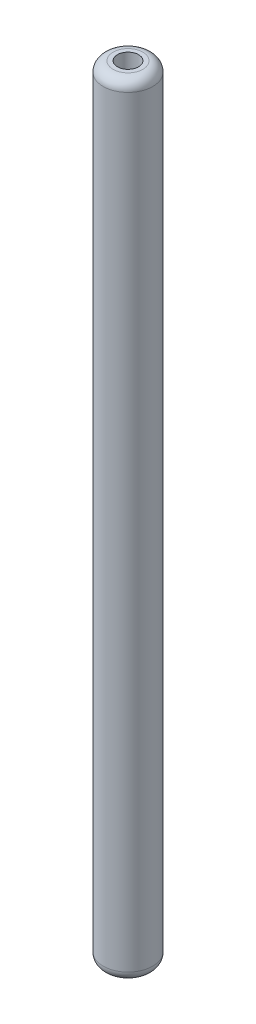
SolidWorks part; units mm, degrees
ref_plane "Front Plane" through (0, 0, 0) normal (0, 0, 1) x (1, 0, 0)
ref_plane "Top Plane" through (0, 0, 0) normal (0, 1, 0) x (1, 0, 0)
ref_plane "Right Plane" through (0, 0, 0) normal (1, 0, 0) x (0, 0, -1)
sketch "Sketch1" plane through (0, 0, 0) normal (0, 1, 0) x (1, 0, 0)
  circle A0 centre (0, 0) radius 6.35
  dimension ".5" = 12.7
extrude "Boss-Extrude1" add sketch "Sketch1" along normal blind 200.025
sketch "Sketch15" plane through (0, 200.025, 0) normal (0, 1, 0) x (1, 0, 0)
  line L0 (0, 6.35) -> (0, -6.35) construction
  line L1 (-6.35, 0) -> (6.35, 0) construction
  circle A0 centre (0, 0) radius 6.35 construction
  point P7 (0, 0)
  point P11 (0, 0)
hole_wizard "1/4-28 Tapped Hole6" positions "3DSketch14" profile "Sketch18" tap size "1/4-28" standard "ANSI Inch"
sketch3d "3DSketch14"
  point P0 (0, 200.025, 0)
sketch "Sketch18" plane through (0, 200.025, 0) normal (1, 0, 0) x (0, 0, 1)
  line L0 (0, 0) -> (0, 31.5974)
  line L1 (0, 31.5974) -> (2.7051, 29.972)
  line L2 (2.7051, 29.972) -> (2.7051, 0)
  line L5 (2.7051, 0) -> (0, 0)
  line L10 (0, 31.5974) -> (-2.7051, 29.972) construction
  line L11 (0, -6.35) -> (0, 107.95) construction
  dimension "Tap Drill Dia." = 5.4102
  dimension "Tap Drill Depth" = 29.972
  dimension "Drill Angle" = 118
cosmetic thread "Hole Thread1" parameters "D1"=25.4, "D2"=6.35
sketch "Sketch21" plane through (0, 0, 0) normal (0, -1, 0) x (-1, 0, 0)
  line L0 (0, 6.35) -> (0, -6.35) construction
  line L1 (-6.35, 0) -> (6.35, 0) construction
  circle A1 centre (0, 0) radius 6.35 construction
  point P7 (0, 0)
  point P11 (0, 0)
hole_wizard "1/4-28 Tapped Hole8" positions "3DSketch15" profile "Sketch22" tap size "1/4-28" standard "ANSI Inch"
sketch3d "3DSketch15"
  point P0 (0, 0, 0)
sketch "Sketch22" plane through (0, 0, 0) normal (1, 0, 0) x (0, 0, -1)
  line L0 (0, 0) -> (0, 31.5974)
  line L1 (0, 31.5974) -> (2.7051, 29.972)
  line L2 (2.7051, 29.972) -> (2.7051, 0)
  line L5 (2.7051, 0) -> (0, 0)
  line L10 (0, 31.5974) -> (-2.7051, 29.972) construction
  line L11 (0, -6.35) -> (0, 107.95) construction
  dimension "Tap Drill Dia." = 5.4102
  dimension "Tap Drill Depth" = 29.972
  dimension "Drill Angle" = 118
cosmetic thread "Hole Thread3" parameters "D1"=25.4, "D2"=6.35
fillet "Fillet4" radius 2.54 1 edges at (0, 200.025, 6.35)
fillet "Fillet5" radius 2.54 1 edges at (0, 0, 6.35)
